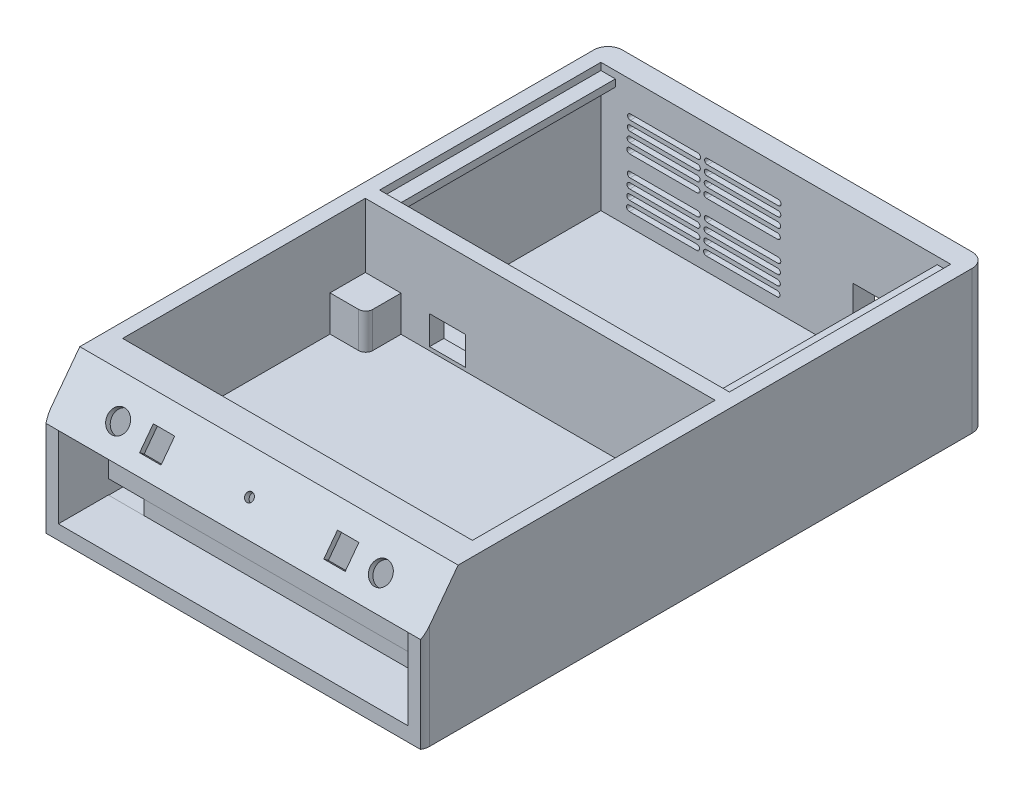
SolidWorks part; units mm, degrees
ref_plane "Front Plane" through (0, 0, 0) normal (0, 0, 1) x (1, 0, 0)
ref_plane "Top Plane" through (0, 0, 0) normal (0, 1, 0) x (1, 0, 0)
ref_plane "Right Plane" through (0, 0, 0) normal (1, 0, 0) x (0, 0, -1)
sketch "Sketch1" plane through (0, 0, 0) normal (0, 1, 0) x (1, 0, 0)
  line L0 (0, -10) -> (0, -390)
  line L1 (10, 0) -> (255, 0)
  line L2 (265, -10) -> (265, -390)
  line L3 (10, -400) -> (255, -400)
  arc A0 (0, -10) -> (10, 0) centre (10, -10) cw
  arc A1 (265, -10) -> (255, 0) centre (255, -10) ccw
  arc A2 (0, -390) -> (10, -400) centre (10, -390) ccw
  arc A3 (265, -390) -> (255, -400) centre (255, -390) cw
extrude "Boss-Extrude2" add sketch "Sketch1" along normal blind 100
ref_plane "Plane1" through (0, 100, 0) normal (0, 1, 0) x (1, 0, 0)
sketch "Sketch4" plane through (0, 100, 0) normal (0, 1, 0) x (1, 0, 0)
  line L0 (0, -10) -> (0, -390) construction
  line L1 (10, -180) -> (255, -180)
  line L2 (10, -180) -> (10, -350)
  line L3 (10, -350) -> (255, -350)
  line L4 (255, -180) -> (255, -350)
  line L5 (10, -400) -> (255, -400) construction
  dimension "D1" = 170
  dimension "D2" = 245
  dimension "D3" = 10
  dimension "D4" = 50
extrude "Cut-Extrude2" cut sketch "Sketch4" against normal blind 70
ref_plane "Plane2" through (132.5, 0, 0) normal (1, 0, 0) x (0, 0, -1)
ref_plane "Plane4" through (0, 0, 360) normal (0, 0, 1) x (1, 0, 0)
sketch "Sketch10" plane through (132.5, 0, 0) normal (1, 0, 0) x (0, 0, -1)
  line L0 (-400, 60) -> (-370, 100)
  line L1 (-400, 100) -> (-400, 0) construction
  line L2 (145.75, 100) -> (-145.75, 100) construction
  line L5 (-360, 55) -> (-360, -55) construction
  line L6 (-400, 60) -> (-400, 100)
  line L7 (-400, 100) -> (-370, 100)
  dimension "D1" = 60
  dimension "D2" = 10
extrude "Cut-Extrude12" cut sketch "Sketch10" against normal through all both and the other way through all
sketch "Sketch14" plane through (132.5, 0, 0) normal (1, 0, 0) x (0, 0, -1)
  line L0 (-390, 10) -> (-360, 10)
  line L1 (-390, 73.3333) -> (-390, 0) construction
  line L2 (-360, 33) -> (-360, -33) construction
  line L7 (-390, 66.6667) -> (-390, 10)
  line L8 (-390, 73.3333) -> (-370, 100) construction
  line L10 (-390, 0) -> (-10, 0) construction
  line L11 (-390, 66.6667) -> (-368, 96)
  line L12 (-368, 96) -> (-360, 96)
  line L13 (-360, 96) -> (-360, 10)
  line L14 (145.75, 100) -> (-145.75, 100) construction
  dimension "D1" = 4
  dimension "D2" = 4
  dimension "D3" = 4
  dimension "D4" = 10
extrude "Cut-Extrude13" cut sketch "Sketch14" against normal mid plane 245
sketch "Sketch15" plane through (132.5, 0, 0) normal (1, 0, 0) x (0, 0, -1)
  line L0 (-360, 55) -> (-360, -55) construction
  line L2 (-360, 9.7841) -> (-360, 20)
  line L3 (-360, 20) -> (-170, 20)
  line L5 (-10, 100) -> (-10, 0) construction
  line L6 (-170, 90) -> (-15, 90)
  line L9 (-15, 90) -> (-15, 10)
  line L11 (-180, 30) -> (-180, 100) construction
  line L12 (145.75, 100) -> (-145.75, 100) construction
  line L13 (-170, 20) -> (-170, 90)
  line L14 (-15, 10) -> (-360, 9.7841)
  dimension "D1" = 10
  dimension "D3" = 5
  dimension "D5" = 10
  dimension "D6" = 10
extrude "Cut-Extrude14" cut sketch "Sketch15" against normal mid plane 245
sketch "Sketch16" plane through (0, 0, 0) normal (0, 0, -1) x (-1, 0, 0)
  line L0 (-134.2706, 77.0723) -> (-84.5977, 77.0723) construction
  line L1 (-134.2706, 79.0076) -> (-84.5977, 79.0076)
  line L2 (-134.2706, 75.137) -> (-84.5977, 75.137)
  line L3 (-77.9316, 77.0723) -> (-30.6241, 77.0723) construction
  line L4 (-77.9316, 79.0076) -> (-30.6241, 79.0076)
  line L5 (-77.9316, 75.137) -> (-30.6241, 75.137)
  line L6 (-134.0625, 70.1912) -> (-84.3896, 70.1912) construction
  line L7 (-134.0625, 72.1265) -> (-84.3896, 72.1265)
  line L8 (-134.0625, 68.2559) -> (-84.3896, 68.2559)
  line L9 (-77.7236, 70.1912) -> (-30.416, 70.1912) construction
  line L10 (-77.7236, 72.1265) -> (-30.416, 72.1265)
  line L11 (-77.7236, 68.2559) -> (-30.416, 68.2559)
  line L12 (-133.955, 63.3101) -> (-84.2821, 63.3101) construction
  line L13 (-133.955, 65.2454) -> (-84.2821, 65.2454)
  line L14 (-133.955, 61.3748) -> (-84.2821, 61.3748)
  line L15 (-77.616, 63.3101) -> (-30.3085, 63.3101) construction
  line L16 (-77.616, 65.2454) -> (-30.3085, 65.2454)
  line L17 (-77.616, 61.3748) -> (-30.3085, 61.3748)
  line L18 (-133.7469, 56.429) -> (-84.074, 56.429) construction
  line L19 (-133.7469, 58.3643) -> (-84.074, 58.3643)
  line L20 (-133.7469, 54.4937) -> (-84.074, 54.4937)
  line L21 (-77.408, 56.429) -> (-30.1004, 56.429) construction
  line L22 (-77.408, 58.3643) -> (-30.1004, 58.3643)
  line L23 (-77.408, 54.4937) -> (-30.1004, 54.4937)
  line L24 (-134.0486, 42.0217) -> (-84.3757, 42.0217) construction
  line L25 (-134.0486, 43.957) -> (-84.3757, 43.957)
  line L26 (-134.0486, 40.0864) -> (-84.3757, 40.0864)
  line L27 (-77.7097, 42.0217) -> (-30.4021, 42.0217) construction
  line L28 (-77.7097, 43.957) -> (-30.4021, 43.957)
  line L29 (-77.7097, 40.0864) -> (-30.4021, 40.0864)
  line L30 (-133.8405, 35.1406) -> (-84.1676, 35.1406) construction
  line L31 (-133.8405, 37.0759) -> (-84.1676, 37.0759)
  line L32 (-133.8405, 33.2053) -> (-84.1676, 33.2053)
  line L33 (-77.5016, 35.1406) -> (-30.194, 35.1406) construction
  line L34 (-77.5016, 37.0759) -> (-30.194, 37.0759)
  line L35 (-77.5016, 33.2053) -> (-30.194, 33.2053)
  line L36 (-133.733, 28.2595) -> (-84.0601, 28.2595) construction
  line L37 (-133.733, 30.1948) -> (-84.0601, 30.1948)
  line L38 (-133.733, 26.3242) -> (-84.0601, 26.3242)
  line L39 (-77.3941, 28.2595) -> (-30.0865, 28.2595) construction
  line L40 (-77.3941, 30.1948) -> (-30.0865, 30.1948)
  line L41 (-77.3941, 26.3242) -> (-30.0865, 26.3242)
  line L42 (-133.5249, 21.3784) -> (-83.852, 21.3784) construction
  line L43 (-133.5249, 23.3137) -> (-83.852, 23.3137)
  line L44 (-133.5249, 19.4431) -> (-83.852, 19.4431)
  line L45 (-77.186, 21.3784) -> (-29.8784, 21.3784) construction
  line L46 (-77.186, 23.3137) -> (-29.8784, 23.3137)
  line L47 (-77.186, 19.4431) -> (-29.8784, 19.4431)
  line L48 (-10, 10) -> (-255, 10) construction
  line L49 (-229.7734, 10) -> (-186.6346, 10)
  line L50 (-229.7734, 10) -> (-229.7734, 54.2535)
  line L51 (-229.7734, 54.2535) -> (-186.6346, 54.2535)
  line L52 (-186.6346, 10) -> (-186.6346, 54.2535)
  arc A0 (-134.2706, 79.0076) -> (-134.2706, 75.137) centre (-134.2706, 77.0723) ccw
  arc A1 (-84.5977, 75.137) -> (-84.5977, 79.0076) centre (-84.5977, 77.0723) ccw
  arc A2 (-77.9316, 79.0076) -> (-77.9316, 75.137) centre (-77.9316, 77.0723) ccw
  arc A3 (-30.6241, 75.137) -> (-30.6241, 79.0076) centre (-30.6241, 77.0723) ccw
  arc A4 (-134.0625, 72.1265) -> (-134.0625, 68.2559) centre (-134.0625, 70.1912) ccw
  arc A5 (-84.3896, 68.2559) -> (-84.3896, 72.1265) centre (-84.3896, 70.1912) ccw
  arc A6 (-77.7236, 72.1265) -> (-77.7236, 68.2559) centre (-77.7236, 70.1912) ccw
  arc A7 (-30.416, 68.2559) -> (-30.416, 72.1265) centre (-30.416, 70.1912) ccw
  arc A8 (-133.955, 65.2454) -> (-133.955, 61.3748) centre (-133.955, 63.3101) ccw
  arc A9 (-84.2821, 61.3748) -> (-84.2821, 65.2454) centre (-84.2821, 63.3101) ccw
  arc A10 (-77.616, 65.2454) -> (-77.616, 61.3748) centre (-77.616, 63.3101) ccw
  arc A11 (-30.3085, 61.3748) -> (-30.3085, 65.2454) centre (-30.3085, 63.3101) ccw
  arc A12 (-133.7469, 58.3643) -> (-133.7469, 54.4937) centre (-133.7469, 56.429) ccw
  arc A13 (-84.074, 54.4937) -> (-84.074, 58.3643) centre (-84.074, 56.429) ccw
  arc A14 (-77.408, 58.3643) -> (-77.408, 54.4937) centre (-77.408, 56.429) ccw
  arc A15 (-30.1004, 54.4937) -> (-30.1004, 58.3643) centre (-30.1004, 56.429) ccw
  arc A16 (-134.0486, 43.957) -> (-134.0486, 40.0864) centre (-134.0486, 42.0217) ccw
  arc A17 (-84.3757, 40.0864) -> (-84.3757, 43.957) centre (-84.3757, 42.0217) ccw
  arc A18 (-77.7097, 43.957) -> (-77.7097, 40.0864) centre (-77.7097, 42.0217) ccw
  arc A19 (-30.4021, 40.0864) -> (-30.4021, 43.957) centre (-30.4021, 42.0217) ccw
  arc A20 (-133.8405, 37.0759) -> (-133.8405, 33.2053) centre (-133.8405, 35.1406) ccw
  arc A21 (-84.1676, 33.2053) -> (-84.1676, 37.0759) centre (-84.1676, 35.1406) ccw
  arc A22 (-77.5016, 37.0759) -> (-77.5016, 33.2053) centre (-77.5016, 35.1406) ccw
  arc A23 (-30.194, 33.2053) -> (-30.194, 37.0759) centre (-30.194, 35.1406) ccw
  arc A24 (-133.733, 30.1948) -> (-133.733, 26.3242) centre (-133.733, 28.2595) ccw
  arc A25 (-84.0601, 26.3242) -> (-84.0601, 30.1948) centre (-84.0601, 28.2595) ccw
  arc A26 (-77.3941, 30.1948) -> (-77.3941, 26.3242) centre (-77.3941, 28.2595) ccw
  arc A27 (-30.0865, 26.3242) -> (-30.0865, 30.1948) centre (-30.0865, 28.2595) ccw
  arc A28 (-133.5249, 23.3137) -> (-133.5249, 19.4431) centre (-133.5249, 21.3784) ccw
  arc A29 (-83.852, 19.4431) -> (-83.852, 23.3137) centre (-83.852, 21.3784) ccw
  arc A30 (-77.186, 23.3137) -> (-77.186, 19.4431) centre (-77.186, 21.3784) ccw
  arc A31 (-29.8784, 19.4431) -> (-29.8784, 23.3137) centre (-29.8784, 21.3784) ccw
  point P2 (-109.4342, 77.0723)
  point P9 (-54.2779, 77.0723)
  point P26 (-109.2261, 70.1912)
  point P33 (-54.0698, 70.1912)
  point P40 (-109.1186, 63.3101)
  point P47 (-53.9623, 63.3101)
  point P54 (-108.9105, 56.429)
  point P61 (-53.7542, 56.429)
  point P68 (-109.2122, 42.0217)
  point P75 (-54.0559, 42.0217)
  point P82 (-109.0041, 35.1406)
  point P89 (-53.8478, 35.1406)
  point P96 (-108.8966, 28.2595)
  point P103 (-53.7403, 28.2595)
  point P110 (-108.6885, 21.3784)
  point P117 (-53.5322, 21.3784)
extrude "Cut-Extrude15" cut sketch "Sketch16" against normal blind 30
sketch "Sketch17" plane through (0, 213.6, 284.8) normal (0, 0.6, 0.8) x (1, 0, 0)
  line L0 (132.5, -55) -> (132.5, 55) construction
  line L1 (60.5, -157) -> (75.5, -157)
  line L2 (60.5, -157) -> (60.5, -173)
  line L3 (60.5, -173) -> (75.5, -173)
  line L4 (75.5, -157) -> (75.5, -173)
  line L5 (189.5, -157) -> (204.5, -157)
  line L6 (189.5, -157) -> (189.5, -173)
  line L7 (189.5, -173) -> (204.5, -173)
  line L8 (204.5, -157) -> (204.5, -173)
  line L9 (0, -142) -> (265, -142) construction
  circle A0 centre (132.5, -164.7277) radius 2.9529
  circle A1 centre (40.5, -164.7277) radius 7.5
  circle A2 centre (224.5, -164.7277) radius 7.5
  point P18 (132.5, -168.3895)
  point P19 (132.5, -164.7277)
  dimension "D9" = 15
  dimension "D10" = 15
  dimension "D1" = 16
  dimension "D2" = 15
  dimension "D3" = 16
  dimension "D4" = 57
  dimension "D5" = 57
  dimension "D6" = 15
  dimension "D7" = 15
  dimension "D8" = 15
  dimension "D11" = 20
  dimension "D12" = 20
extrude "Cut-Extrude16" cut sketch "Sketch17" against normal blind 10
sketch "Sketch18" plane through (0, 30, 0) normal (0, 1, 0) x (1, 0, 0)
  line L0 (10, -180) -> (10, -204.7299)
  line L1 (10, -180) -> (10, -350) construction
  line L2 (10, -204.7299) -> (30, -204.7299)
  line L3 (10, -180) -> (34.9927, -180)
  line L4 (34.9927, -180) -> (34.9927, -200)
  line L5 (255, -350) -> (255, -324.1491)
  line L6 (255, -350) -> (255, -180) construction
  line L7 (255, -324.1491) -> (235, -324.1491)
  line L8 (255, -350) -> (230.0729, -350)
  line L9 (10, -350) -> (255, -350) construction
  line L10 (230.0729, -350) -> (230.0729, -330)
  arc A0 (30, -204.7299) -> (34.9927, -200) centre (30, -199.7299) ccw
  arc A1 (235, -324.1491) -> (230.0729, -330) centre (235, -329.1491) ccw
  dimension "D1" = 5
  dimension "D2" = 20
  dimension "D3" = 20
  dimension "D4" = 5
  dimension "D5" = 20
  dimension "D6" = 20
extrude "Boss-Extrude3" add sketch "Sketch18" along normal blind 25
sketch "Sketch19" plane through (0, 0, 180) normal (0, 0, 1) x (1, 0, 0)
  line L0 (10, 55) -> (30, 55) construction
  line L3 (54.9927, 52.5) -> (79.9927, 52.5)
  line L5 (54.9927, 32.5) -> (79.9927, 32.5)
  line L6 (54.9927, 52.5) -> (54.9927, 32.5)
  line L7 (79.9927, 32.5) -> (79.9927, 52.5)
  line L8 (10, 30) -> (230.0729, 30) construction
  line L9 (34.9927, 55) -> (34.9927, 30) construction
  dimension "D1" = 2.5
  dimension "D2" = 2.5
  dimension "D3" = 25
  dimension "D4" = 20
extrude "Cut-Extrude17" cut sketch "Sketch19" against normal blind 15
sketch "Sketch21" plane through (0, 20, 0) normal (0, -1, 0) x (1, 0, 0)
  line L9 (10, 170) -> (255, 170) construction
  line L10 (34.9927, 170) -> (230.0729, 170)
  line L11 (34.9927, 170) -> (34.9927, 360)
  line L12 (34.9927, 360) -> (230.0729, 360)
  line L13 (230.0729, 170) -> (230.0729, 360)
  line L14 (55, 360) -> (-55, 360) construction
extrude "Boss-Extrude9" add sketch "Sketch21" along normal blind 10 separate body
sketch "Sketch22" plane through (0, 0, 400) normal (0, 0, 1) x (1, 0, 0)
  line L1 (0, 0) -> (265, 0)
  line L2 (0, 0) -> (0, 73.3333)
  line L3 (0, 73.3333) -> (265, 73.3333)
  line L4 (265, 0) -> (265, 73.3333)
extrude "Cut-Extrude18" cut sketch "Sketch22" against normal blind 5
sketch "Sketch23" plane through (0, 0, 395) normal (0, 0, 1) x (1, 0, 0)
  line L1 (10, 10) -> (255, 10)
  line L2 (10, 10) -> (10, 66.6667)
  line L3 (10, 66.6667) -> (255, 66.6667)
  line L4 (255, 10) -> (255, 66.6667)
extrude "Cut-Extrude19" cut sketch "Sketch23" against normal blind 5
sketch "Sketch24" plane through (0, 100, 0) normal (0, 1, 0) x (1, 0, 0)
sketch "Sketch25" plane through (0, 100, 0) normal (0, 1, 0) x (1, 0, 0)
  line L1 (10, -170) -> (255, -170)
  line L2 (10, -170) -> (10, -15)
  line L3 (10, -15) -> (255, -15)
  line L4 (255, -170) -> (255, -15)
extrude "Cut-Extrude20" cut sketch "Sketch25" against normal blind 5
sketch "Sketch26" plane through (0, 95, 0) normal (0, 1, 0) x (1, 0, 0)
  line L0 (10, -170) -> (255, -170) construction
  line L1 (20.146, -170) -> (245.542, -170)
  line L2 (20.146, -170) -> (20.146, -15)
  line L3 (20.146, -15) -> (245.542, -15)
  line L4 (245.542, -170) -> (245.542, -15)
  line L5 (255, -15) -> (10, -15) construction
extrude "Cut-Extrude21" cut sketch "Sketch26" against normal blind 5
